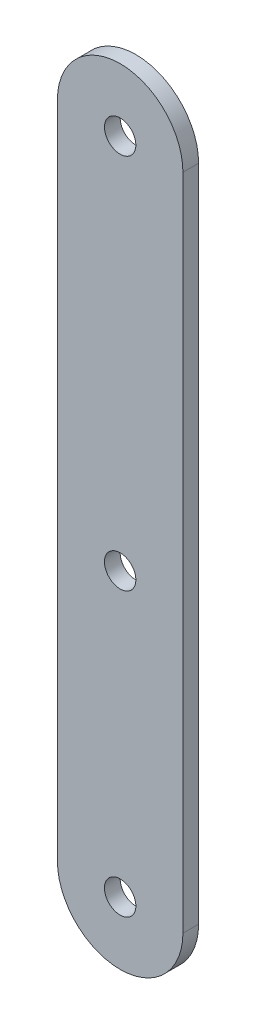
SolidWorks part; units mm, degrees
material "5052-H32"
ref_plane "Front Plane" through (0, 0, 0) normal (0, 0, 1) x (1, 0, 0)
ref_plane "Top Plane" through (0, 0, 0) normal (0, 1, 0) x (1, 0, 0)
ref_plane "Right Plane" through (0, 0, 0) normal (1, 0, 0) x (0, 0, -1)
sketch "Sketch1" plane through (0, 0, 0) normal (0, 0, 1) x (1, 0, 0)
  line L0 (-50.8, -533.4) -> (-50.8, 0)
  line L1 (50.8, 0) -> (50.8, -533.4)
  line L2 (0, 0) -> (0, -304.8) construction
  arc A0 (50.8, 0) -> (-50.8, 0) centre (0, 0) ccw
  arc A1 (-50.8, -533.4) -> (50.8, -533.4) centre (0, -533.4) ccw
  circle A2 centre (0, 0) radius 12.7
  circle A3 centre (0, -533.4) radius 12.7
  circle A5 centre (0, -304.8) radius 12.7
  dimension "D1" = 50.8
  dimension "D3" = 25.4
  dimension "D4" = 25.4
  dimension "D5" = 304.8
  dimension "D2" = 533.4
extrude "Boss-Extrude1" add sketch "Sketch1" along normal blind 12.7
sketch "Sketch2" plane through (0, 0, 12.7) normal (0, 0, 1) x (1, 0, 0)
  line L0 (45.1941, -296.5123) -> (50.8, -1235.4744)
  line L1 (50.8, -533.4) -> (50.8, 0) construction
  line L3 (50.8, -1235.4744) -> (50.8, -280.2333)
  line L4 (45.1941, -296.5123) -> (0, -296.5123) construction
  line L5 (0, -296.5123) -> (0, 0) construction
  line L7 (52.6331, -278.4002) -> (50.8, -280.2333)
  arc A1 (52.6331, -278.4002) -> (45.1941, -296.5123) centre (70.5936, -296.3607) ccw
  dimension "D3" = 25.4
  dimension "D1" = 296.5123
  dimension "D2" = 70.5938
  dimension "D4" = 45
  dimension "D5" = 938.9621
extrude "Cut-Extrude1" [suppressed] cut sketch "Sketch2" against normal through all
